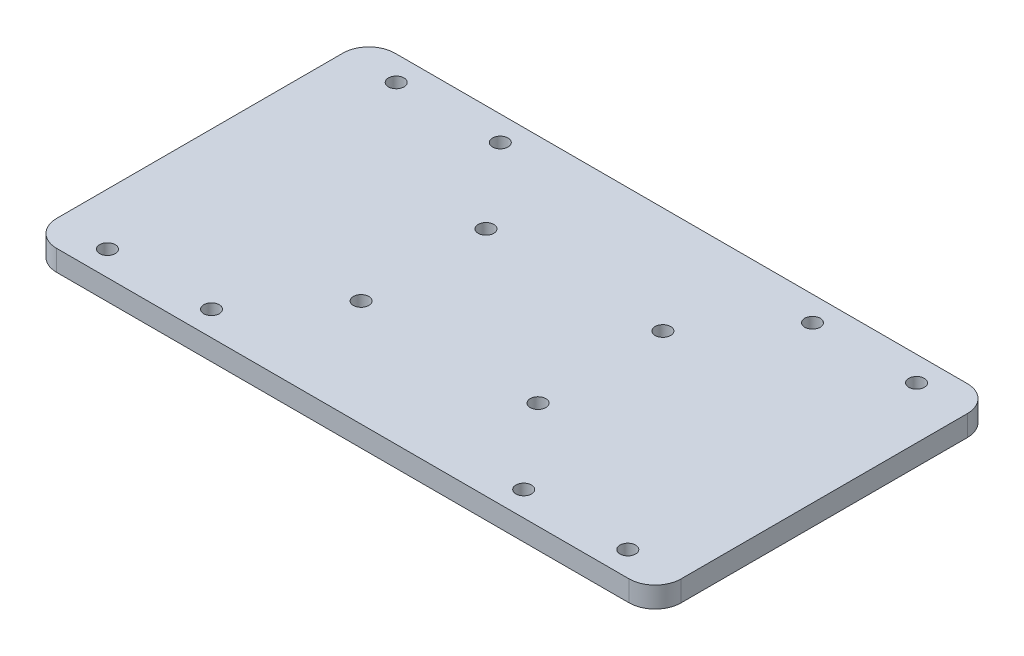
SolidWorks part; units mm, degrees
ref_plane "前视基准面" through (0, 0, 0) normal (0, 0, 1) x (1, 0, 0)
ref_plane "上视基准面" through (0, 0, 0) normal (0, 1, 0) x (1, 0, 0)
ref_plane "右视基准面" through (0, 0, 0) normal (1, 0, 0) x (0, 0, -1)
other "Configuration Table"
sketch "草图1" plane through (0, 0, 0) normal (0, 1, 0) x (1, 0, 0)
  line L1 (-60, -32.5) -> (60, -32.5)
  line L2 (-60, -32.5) -> (-60, 32.5)
  line L3 (-60, 32.5) -> (60, 32.5)
  line L4 (60, -32.5) -> (60, 32.5)
  line L5 (-60, -32.5) -> (60, 32.5) construction
  line L6 (-60, 32.5) -> (60, -32.5) construction
  point P0 (0, 0)
  dimension "D1" = 65
  dimension "D2" = 120
extrude "凸台-拉伸1" add sketch "草图1" along normal blind 4
sketch "草图2" plane through (0, 4, 0) normal (0, 1, 0) x (1, 0, 0)
  line L1 (30, 27.75) -> (50, 27.75) construction
  line L2 (30, 27.75) -> (30, -27.75) construction
  line L3 (30, -27.75) -> (50, -27.75) construction
  line L4 (50, 27.75) -> (50, -27.75) construction
  line L5 (60, -32.5) -> (60, 32.5) construction
  line L6 (0, 0) -> (30, 0) construction
  circle A0 centre (50, -27.75) radius 1.5
  circle A1 centre (50, 27.75) radius 1.5
  circle A2 centre (30, 27.75) radius 1.5
  circle A3 centre (30, -27.75) radius 1.5
  dimension "D5" = 3
  dimension "D1" = 20
  dimension "D2" = 55.5
  dimension "D4" = 10
extrude "切除-拉伸1" cut sketch "草图2" against normal blind 4
mirror "镜向2" about plane through (0, 0, 0) normal (1, 0, 0) of "切除-拉伸1"
fillet "圆角1" radius 5 4 edges at (-60, 2, 32.5) (60, 2, 32.5) (60, 2, -32.5) (-60, 2, -32.5)
sketch "草图3" plane through (0, 0, 0) normal (0, -1, 0) x (1, 0, 0)
  circle A0 centre (-17, 12) radius 1.5
  circle A1 centre (17, 12) radius 1.5
  circle A2 centre (17, -12) radius 1.5
  circle A3 centre (-17, -12) radius 1.5
  dimension "D1" = 3
extrude "切除-拉伸2" cut sketch "草图3" against normal through all
